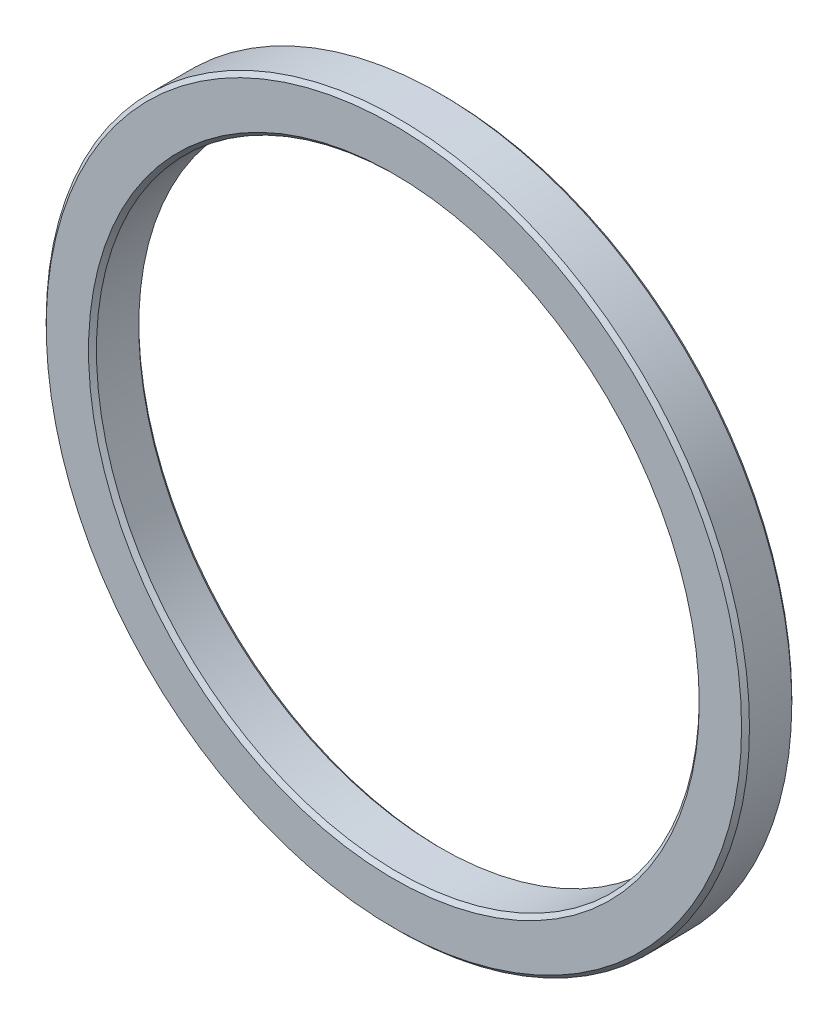
SolidWorks part; units mm, degrees
ref_plane "前视基准面" through (0, 0, 0) normal (0, 0, 1) x (1, 0, 0)
ref_plane "上视基准面" through (0, 0, 0) normal (0, 1, 0) x (1, 0, 0)
ref_plane "右视基准面" through (0, 0, 0) normal (1, 0, 0) x (0, 0, -1)
sketch "草图1" plane through (0, 0, 0) normal (0, 0, 1) x (1, 0, 0)
  circle A0 centre (0, 0) radius 38.1
  circle A1 centre (0, 0) radius 44.45
  dimension "D1" = 76.2
  dimension "D2" = 88.9
extrude "凸台-拉伸1" add sketch "草图1" along normal blind 6.35
chamfer "倒角1" distance 0.5 angle 45 4 edges at (38.1, 0, 0) (44.45, 0, 0) (38.1, 0, 6.35) (44.45, 0, 6.35)
